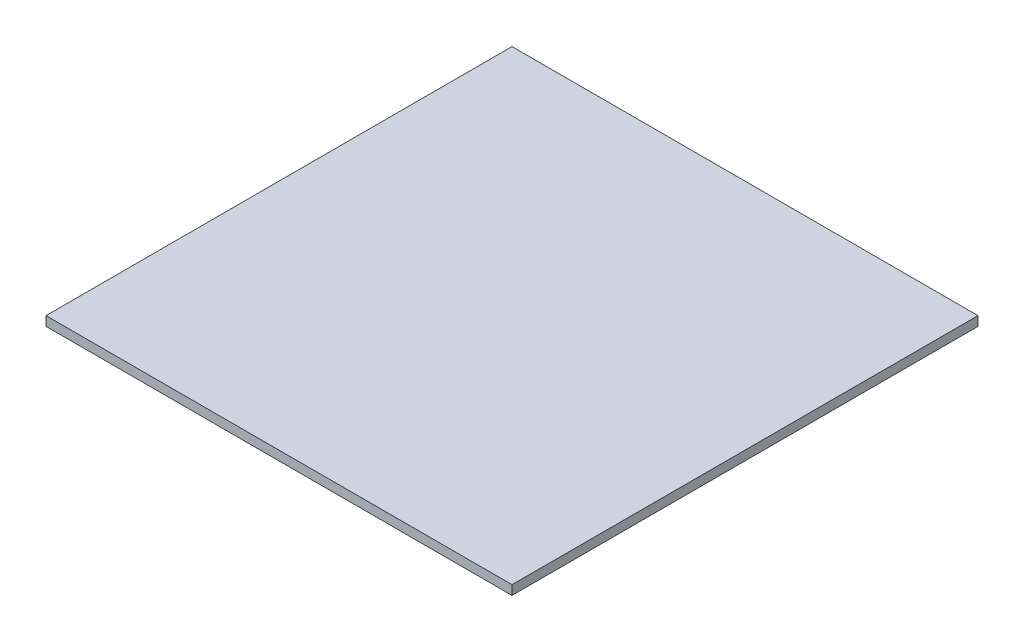
SolidWorks part; units mm, degrees
ref_plane "Plano frontal" through (0, 0, 0) normal (0, 0, 1) x (1, 0, 0)
ref_plane "Plano superior" through (0, 0, 0) normal (0, 1, 0) x (1, 0, 0)
ref_plane "Plano direito" through (0, 0, 0) normal (1, 0, 0) x (0, 0, -1)
sketch "Esboço2" plane through (0, 0, 0) normal (0, 1, 0) x (1, 0, 0)
  line L1 (0, 0) -> (500, 0)
  line L2 (0, 0) -> (0, 500)
  line L3 (0, 500) -> (500, 500)
  line L4 (500, 0) -> (500, 500)
  dimension "D1" = 500
  dimension "D2" = 500
extrude "Ressalto-extrusão1" add sketch "Esboço2" along normal blind 10
